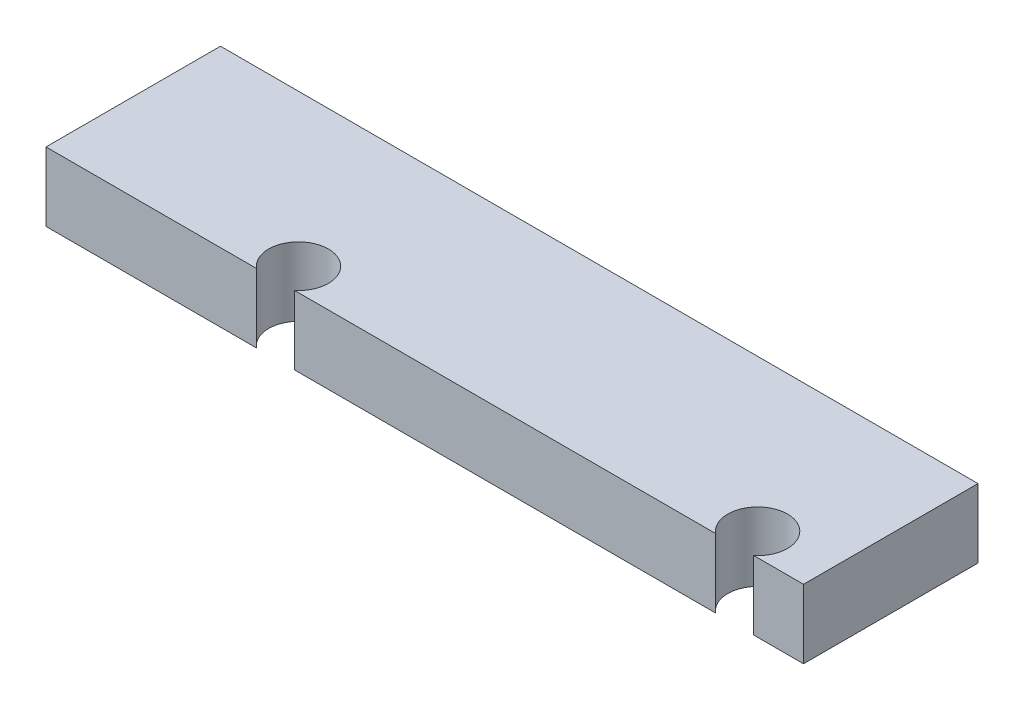
SolidWorks part; units mm, degrees
material "Plain Carbon Steel"
ref_plane "Front Plane" through (0, 0, 0) normal (0, 0, 1) x (1, 0, 0)
ref_plane "Top Plane" through (0, 0, 0) normal (0, 1, 0) x (1, 0, 0)
ref_plane "Right Plane" through (0, 0, 0) normal (1, 0, 0) x (0, 0, -1)
sketch "Sketch1" plane through (0, 0, 0) normal (0, 1, 0) x (1, 0, 0)
  line L0 (0, 0) -> (0, 155.1713) construction
  line L1 (-82.5, -19) -> (82.5, -19)
  line L2 (-82.5, -19) -> (-82.5, 19)
  line L3 (-82.5, 19) -> (82.5, 19)
  line L4 (82.5, -19) -> (82.5, 19)
  line L5 (-82.5, -19) -> (82.5, 19) construction
  line L6 (-82.5, 19) -> (82.5, -19) construction
  line L7 (0, 0) -> (-128.9943, 0) construction
  circle A0 centre (0, 0) radius 17.5 construction
  point P0 (0, 0)
  dimension "D3" = 35
  dimension "D1" = 165
  dimension "D2" = 38
extrude "Boss-Extrude1" add sketch "Sketch1" along normal mid plane 15
sketch "Sketch2" plane through (0, 7.5, 0) normal (0, 1, 0) x (1, 0, 0)
  circle A0 centre (67.5, -14) radius 6.5 construction
  circle A1 centre (67.5, -14) radius 6.5
  circle A2 centre (-32.5, -14) radius 6.5 construction
  circle A3 centre (-32.5, -14) radius 6.5
extrude "Cut-Extrude1" cut sketch "Sketch2" against normal through all
